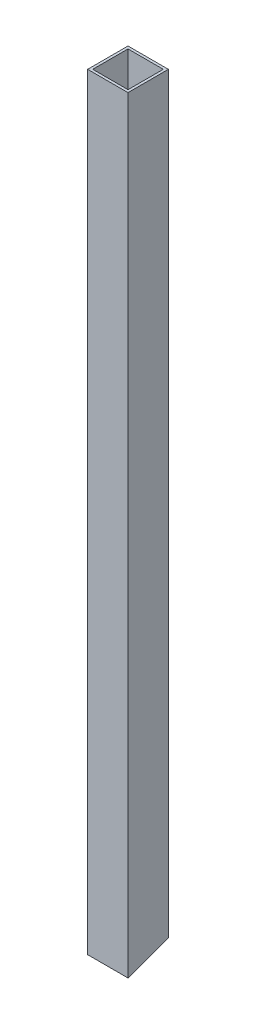
SolidWorks part; units mm, degrees
ref_plane "Front Plane" through (0, 0, 0) normal (0, 0, 1) x (1, 0, 0)
ref_plane "Top Plane" through (0, 0, 0) normal (0, 1, 0) x (1, 0, 0)
ref_plane "Right Plane" through (0, 0, 0) normal (1, 0, 0) x (0, 0, -1)
sketch "Sketch1" plane through (0, 0, 0) normal (0, 1, 0) x (1, 0, 0)
  line L1 (12.7, 12.7) -> (-12.7, 12.7)
  line L2 (12.7, 12.7) -> (12.7, -12.7)
  line L3 (12.7, -12.7) -> (-12.7, -12.7)
  line L4 (-12.7, 12.7) -> (-12.7, -12.7)
  line L5 (12.7, 12.7) -> (-12.7, -12.7) construction
  line L6 (12.7, -12.7) -> (-12.7, 12.7) construction
  line L7 (11.1125, -11.1125) -> (-11.1125, -11.1125)
  line L8 (11.1125, -11.1125) -> (11.1125, 11.1125)
  line L9 (11.1125, 11.1125) -> (-11.1125, 11.1125)
  line L10 (-11.1125, -11.1125) -> (-11.1125, 11.1125)
  line L11 (11.1125, -11.1125) -> (-11.1125, 11.1125) construction
  line L12 (11.1125, 11.1125) -> (-11.1125, -11.1125) construction
  point P0 (0, 0)
  point P6 (0, 0)
  dimension "D1" = 25.4
  dimension "D2" = 25.4
  dimension "D3" = 1.5875
  dimension "D4" = 1.5875
extrude "Boss-Extrude1" add sketch "Sketch1" along normal blind 482.6
sketch "Sketch2" plane through (12.7, 0, 0) normal (1, 0, 0) x (0, 0, -1)
  line L0 (-12.7, 0) -> (12.7, 9.2448)
  line L1 (12.7, 482.6) -> (12.7, 0) construction
  line L2 (12.7, 9.2448) -> (12.7, 0)
  line L3 (-12.7, 0) -> (12.7, 0) construction
  line L4 (12.7, 0) -> (-12.7, 0)
  dimension "D1" = 20
extrude "Cut-Extrude1" cut sketch "Sketch2" against normal blind 482.6
